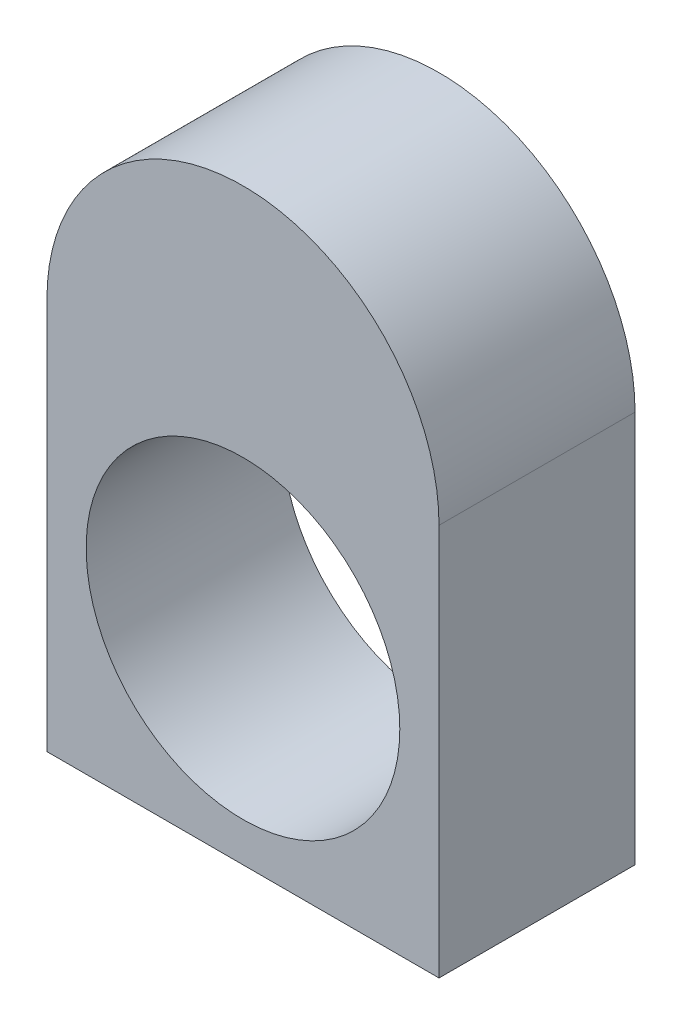
SolidWorks part; units mm, degrees
ref_plane "Front Plane" through (0, 0, 0) normal (0, 0, 1) x (1, 0, 0)
ref_plane "Top Plane" through (0, 0, 0) normal (0, 1, 0) x (1, 0, 0)
ref_plane "Right Plane" through (0, 0, 0) normal (1, 0, 0) x (0, 0, -1)
sketch "Sketch2" plane through (0, 0, 0) normal (0, 0, 1) x (1, 0, 0)
  line L1 (1, -1) -> (-1, -1)
  line L2 (1, -1) -> (1, 1)
  line L3 (1, 1) -> (-1, 1)
  line L4 (-1, -1) -> (-1, 1)
  point P4 (2, 2)
  dimension "D1" = 2
  dimension "D2" = 2
  dimension "D3" = 1
  dimension "D4" = 1
extrude "Boss-Extrude1" add sketch "Sketch2" against normal blind 1
sketch "Sketch3" plane through (0, 0, 0) normal (0, 0, 1) x (1, 0, 0)
  line L0 (1, 1) -> (-1, 1) construction
  circle A0 centre (0, 1) radius 1
extrude "Boss-Extrude2" add sketch "Sketch3" against normal blind 1
sketch "Sketch1" plane through (0, 0, 0) normal (0, 0, 1) x (1, 0, 0)
  circle A0 centre (0, 0) radius 0.8
  dimension "D1" = 1.6
extrude "Cut-Extrude1" cut sketch "Sketch1" against normal blind 1
